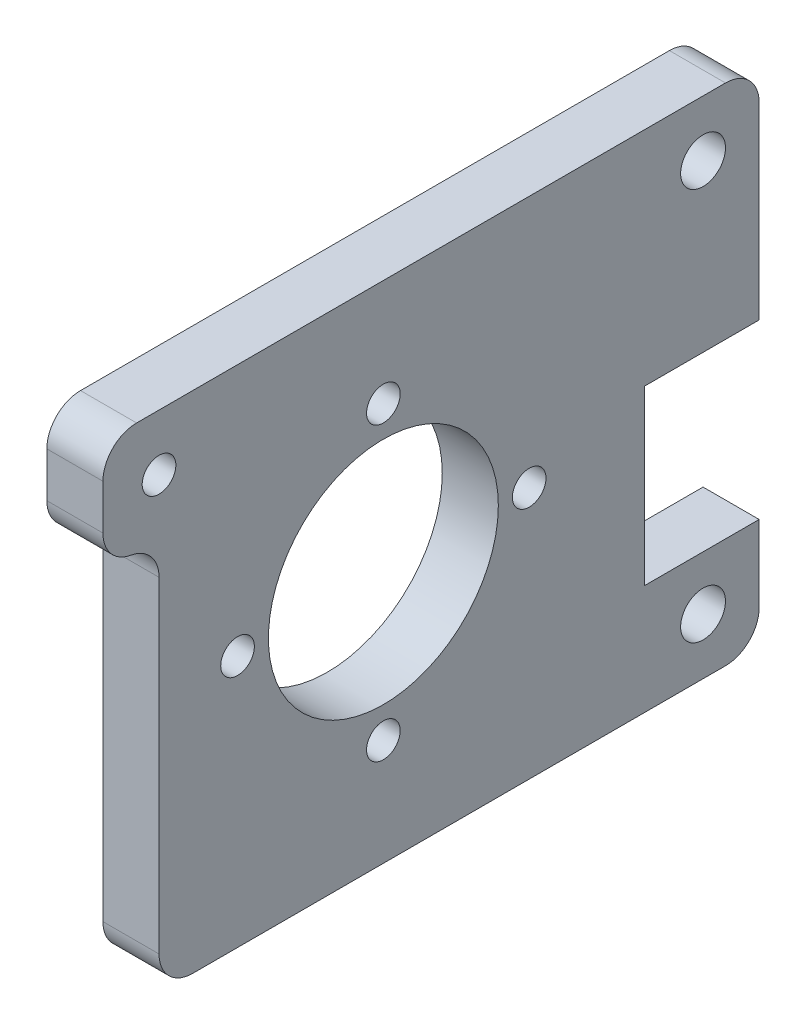
SolidWorks part; units mm, degrees
material "ﾎﾟﾘ塩化ﾋﾞﾆﾙ(PVC)硬質"
ref_plane "正面" through (0, 0, 0) normal (0, 0, 1) x (1, 0, 0)
ref_plane "平面" through (0, 0, 0) normal (0, 1, 0) x (1, 0, 0)
ref_plane "右側面" through (0, 0, 0) normal (1, 0, 0) x (0, 0, -1)
sketch "ｽｹｯﾁ1" plane through (0, 0, 0) normal (1, 0, 0) x (0, 0, -1)
  line L0 (-26.75, 0) -> (26.75, 0) construction
  line L1 (-26.75, -22.5) -> (26.75, -22.5)
  line L2 (-26.75, -22.5) -> (-26.75, 22.5)
  line L3 (-26.75, 22.5) -> (26.75, 22.5)
  line L4 (26.75, -22.5) -> (26.75, 22.5)
  line L5 (-26.75, -22.5) -> (26.75, 22.5) construction
  line L6 (-26.75, 22.5) -> (26.75, -22.5) construction
  line L7 (-6.75, 13) -> (-6.75, -13) construction
  circle A0 centre (-6.75, 0) radius 10.25
  circle A6 centre (21.75, 17.5) radius 2
  circle A7 centre (21.75, -17.5) radius 2
  circle A16 centre (-6.75, 0) radius 13 construction
  circle A17 centre (6.25, 0) radius 1.5
  circle A18 centre (-19.75, 0) radius 1.5
  circle A19 centre (-6.75, 13) radius 1.5
  circle A20 centre (-6.75, -13) radius 1.5
  point P0 (0, 0)
  dimension "D1" = 20.5
  dimension "D2" = 20
  dimension "D4" = 17.5
  dimension "D7" = 5
  dimension "D8" = 5
  dimension "D9" = 4
  dimension "D3" = 26
  dimension "D5" = 3
  dimension "D10" = 53.5
extrude "ﾎﾞｽ - 押し出し1" add sketch "ｽｹｯﾁ1" along normal blind 5
sketch "ｽｹｯﾁ3" plane through (5, 0, 0) normal (1, 0, 0) x (0, 0, -1)
  line L1 (-31.75, 12.5) -> (-26.75, 12.5)
  line L2 (-31.75, 12.5) -> (-31.75, 22.5)
  line L3 (-31.75, 22.5) -> (-26.75, 22.5)
  line L4 (-26.75, 12.5) -> (-26.75, 22.5)
  line L5 (-31.75, 12.5) -> (-26.75, 22.5) construction
  line L6 (-31.75, 22.5) -> (-26.75, 12.5) construction
  point P0 (-29.25, 17.5)
  dimension "D1" = 5
  dimension "D2" = 10
extrude "ﾎﾞｽ - 押し出し2" add sketch "ｽｹｯﾁ3" against normal up to surface (5 mm away) up to face at (0, -17.5, -19.75)
sketch "ｽｹｯﾁ4" plane through (5, 0, 0) normal (1, 0, 0) x (0, 0, -1)
  line L0 (-41.75, 17.5) -> (49958.25, 17.5) construction
  line L1 (-31.75, 22.5) -> (-31.75, 12.5) construction
  line L2 (21.75, 25) -> (21.75, -49975) construction
  line L3 (0, 0) -> (50000, 0) construction
  line L5 (16.55, -12.7) -> (26.95, -12.7)
  line L6 (16.55, -12.7) -> (16.55, 2.7)
  line L7 (16.55, 2.7) -> (26.95, 2.7)
  line L8 (26.95, -12.7) -> (26.95, 2.7)
  line L9 (16.55, -12.7) -> (26.95, 2.7) construction
  line L10 (16.55, 2.7) -> (26.95, -12.7) construction
  circle A0 centre (-26.75, 17.5) radius 1.5
  circle A4 centre (21.75, -17.5) radius 2 construction
  point P4 (-31.75, 17.5)
  point P10 (21.75, -5)
  dimension "D1" = 5
  dimension "D2" = 3
  dimension "D3" = 12.5
  dimension "D4" = 15.4
  dimension "D5" = 10.4
extrude "ｶｯﾄ - 押し出し2" cut sketch "ｽｹｯﾁ4" against normal through all
fillet "ﾌｨﾚｯﾄ1" radius 3 5 edges at (2.5, 22.5, -26.75) (2.5, -22.5, -26.75) (2.5, -22.5, 26.75) (2.5, 12.5, 31.75) (2.5, 22.5, 31.75)
fillet "ﾌｨﾚｯﾄ2" radius 3 1 edges at (2.5, 12.5, 26.75)
